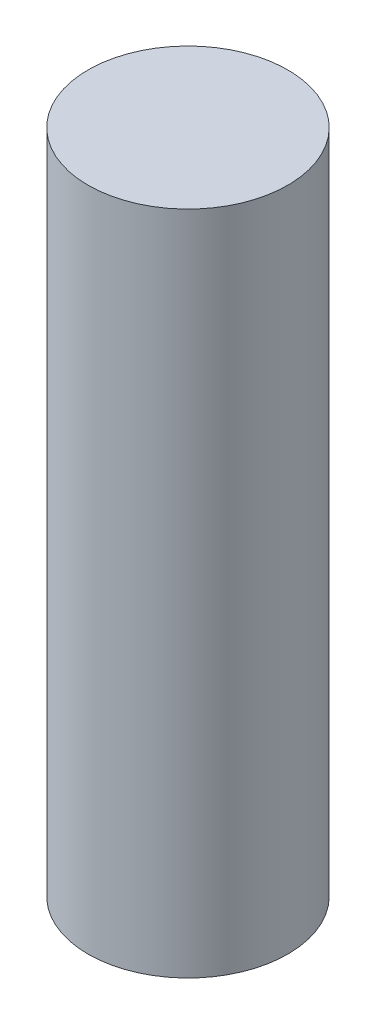
SolidWorks part; units mm, degrees
ref_plane "Front Plane" through (0, 0, 0) normal (0, 0, 1) x (1, 0, 0)
ref_plane "Top Plane" through (0, 0, 0) normal (0, 1, 0) x (1, 0, 0)
ref_plane "Right Plane" through (0, 0, 0) normal (1, 0, 0) x (0, 0, -1)
sketch "Sketch2" plane through (0, 0, 0) normal (0, 1, 0) x (1, 0, 0)
  circle A0 centre (0, 0) radius 9.525
  dimension "D1" = 19.05
extrude "Boss-Extrude1" add sketch "Sketch2" along normal blind 63.5
